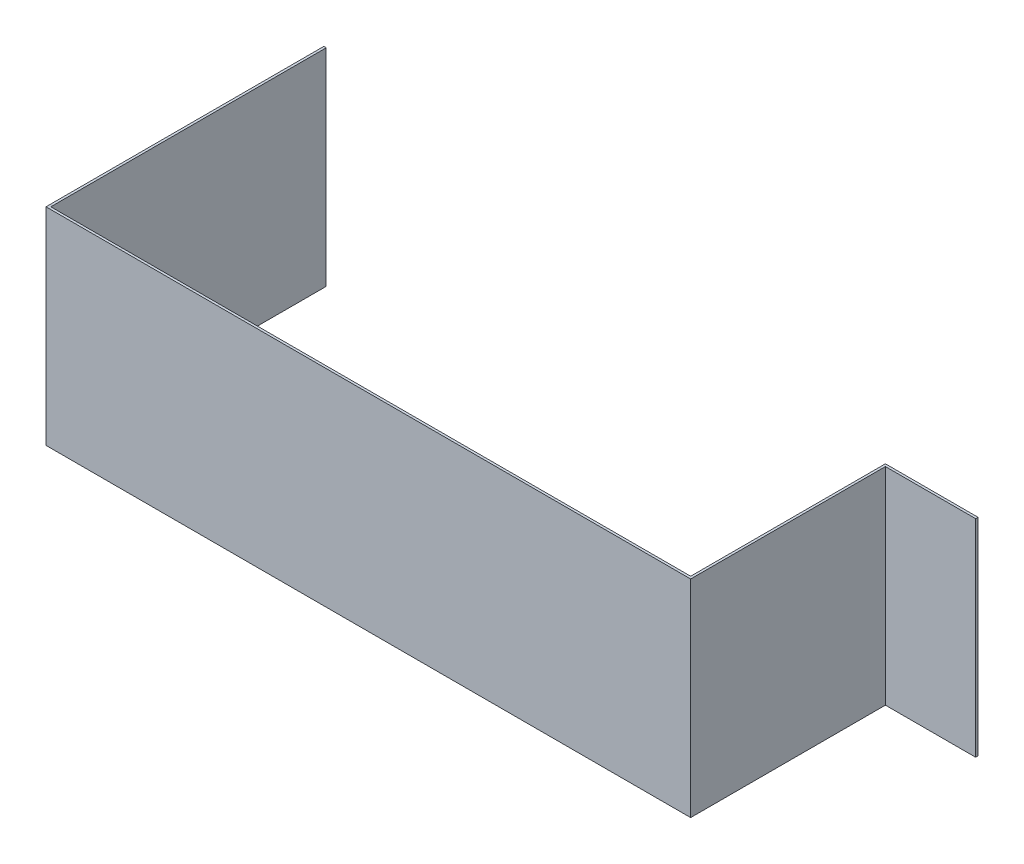
SolidWorks part; units mm, degrees
ref_plane "Front Plane" through (0, 0, 0) normal (0, 0, 1) x (1, 0, 0)
ref_plane "Top Plane" through (0, 0, 0) normal (0, 1, 0) x (1, 0, 0)
ref_plane "Right Plane" through (0, 0, 0) normal (1, 0, 0) x (0, 0, -1)
ref_plane "Plane_y3_2" through (0, 3.2, 0) normal (0, 1, 0) x (1, 0, 0)
sketch "Sketch1" plane through (0, 3.2, 0) normal (0, 1, 0) x (1, 0, 0)
  line L0 (54.525, -4.6) -> (54.525, -22.075)
  line L1 (54.525, -22.075) -> (95.075, -22.075)
  line L2 (95.075, -22.075) -> (95.075, -9.825)
  line L3 (95.075, -9.825) -> (100.75, -9.825)
  line L4 (100.75, -9.825) -> (100.75, -9.675)
  line L5 (100.75, -9.675) -> (94.925, -9.675)
  line L6 (94.925, -9.675) -> (94.925, -21.925)
  line L7 (94.925, -21.925) -> (54.675, -21.925)
  line L8 (54.675, -21.925) -> (54.675, -4.6)
  line L9 (54.675, -4.6) -> (54.525, -4.6)
extrude "Ribbon" add sketch "Sketch1" along normal blind 13
